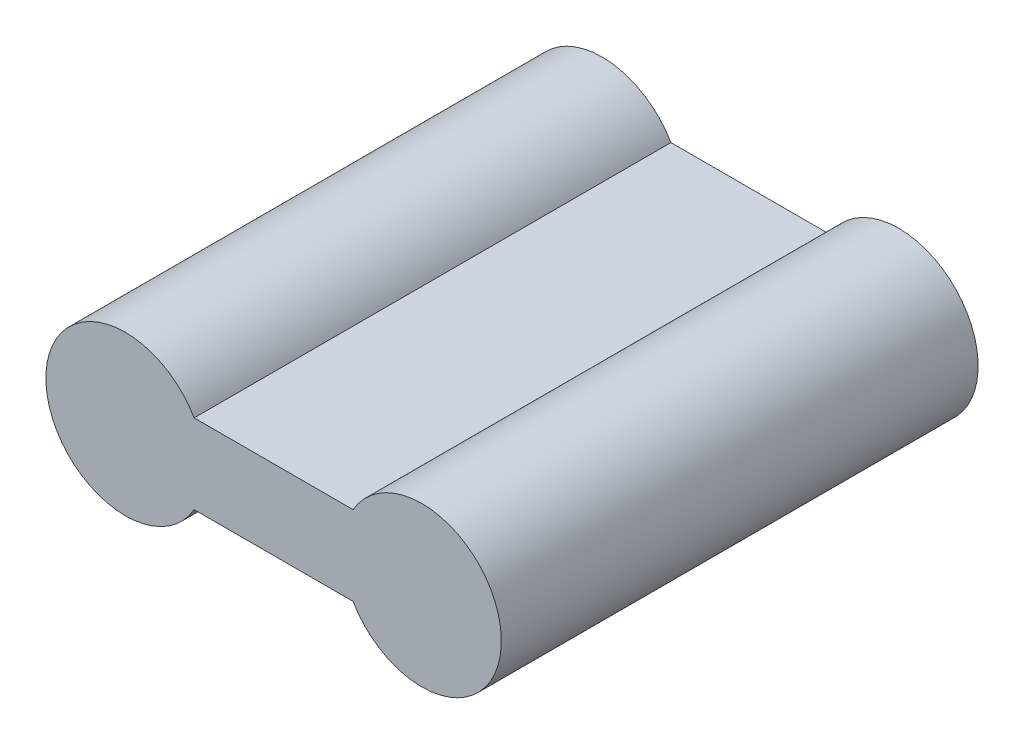
SolidWorks part; units mm, degrees
ref_plane "Plan de face" through (0, 0, 0) normal (0, 0, 1) x (1, 0, 0)
ref_plane "Plan de dessus" through (0, 0, 0) normal (0, 1, 0) x (1, 0, 0)
ref_plane "Plan de droite" through (0, 0, 0) normal (1, 0, 0) x (0, 0, -1)
sketch "Esquisse1" plane through (0, 0, 0) normal (0, 0, 1) x (1, 0, 0)
  line L0 (-2, 0) -> (2, 0)
  line L1 (-2, 2) -> (2, 2)
  line L2 (0, 0) -> (0, 2) construction
  arc A0 (2, 2) -> (2, 0) centre (3.7321, 1) cw
  arc A1 (-2, 2) -> (-2, 0) centre (-3.7321, 1) ccw
  dimension "D1" = 2
  dimension "D2" = 2
  dimension "D3" = 2
extrude "Boss.-Extru.1" add sketch "Esquisse1" along normal blind 12
